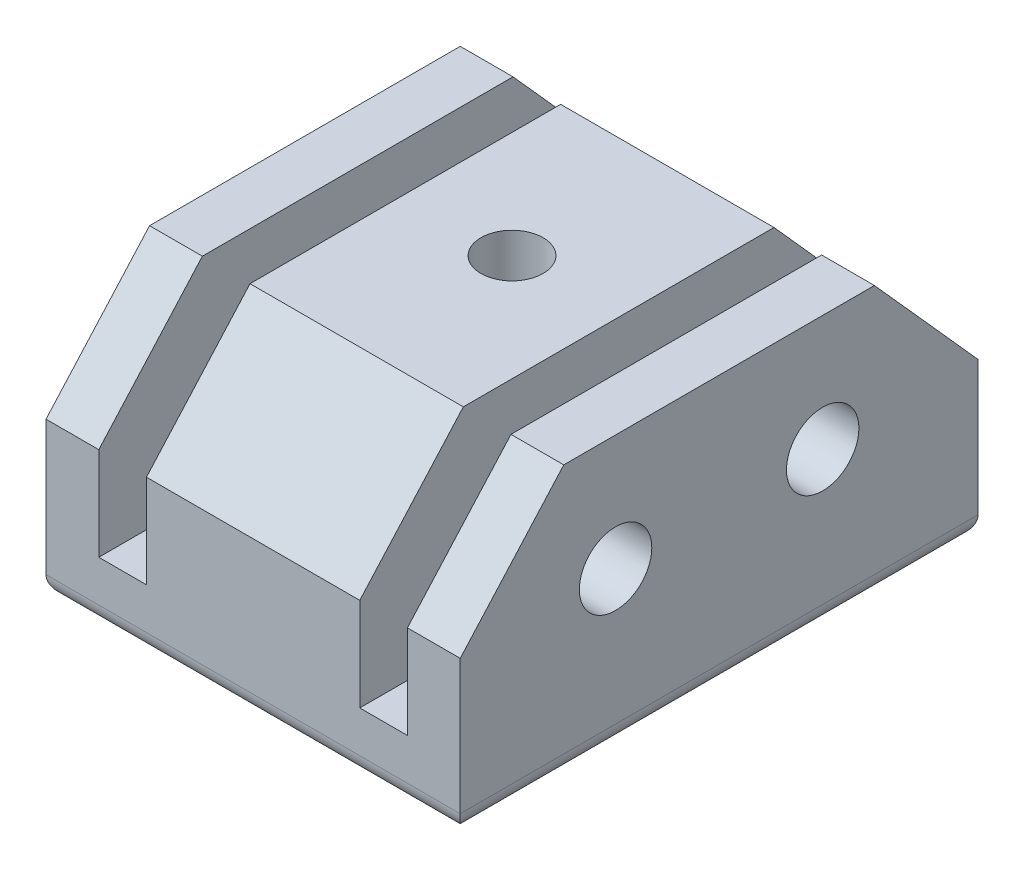
SolidWorks part; units mm, degrees
ref_plane "Front Plane" through (0, 0, 0) normal (0, 0, 1) x (1, 0, 0)
ref_plane "Top Plane" through (0, 0, 0) normal (0, 1, 0) x (1, 0, 0)
ref_plane "Right Plane" through (0, 0, 0) normal (1, 0, 0) x (0, 0, -1)
ref_plane "Plane3" through (-25.4, 0, 0) normal (1, 0, 0) x (0, 0, -1)
sketch "Sketch1" plane through (0, 0, 0) normal (1, 0, 0) x (0, 0, -1)
  line L1 (0, 0) -> (63.5, 0)
  line L2 (0, 0) -> (0, 6.35)
  line L3 (0, 6.35) -> (63.5, 6.35)
  line L4 (63.5, 0) -> (63.5, 6.35)
  dimension "D1" = 6.35
  dimension "D2" = 63.5
extrude "Boss-Extrude1" add sketch "Sketch1" against normal blind 50.8
sketch "Sketch2" plane through (0, 0, 0) normal (1, 0, 0) x (0, 0, -1)
  line L0 (0, 6.35) -> (0, 19.05)
  line L1 (0, 19.05) -> (12.7, 33.249)
  line L2 (12.7, 33.249) -> (50.8, 33.249)
  line L3 (50.8, 33.249) -> (63.5, 19.05)
  line L4 (63.5, 19.05) -> (63.5, 6.35)
  line L5 (63.5, 6.35) -> (0, 6.35)
  point P7 (31.75, 33.249)
  point P10 (31.75, 6.35)
  dimension "D1" = 38.1
  dimension "D2" = 12.7
  dimension "D3" = 12.7
  dimension "D4" = 19.05
  dimension "D5" = 19.05
extrude "Boss-Extrude2" add sketch "Sketch2" against normal blind 50.8
sketch "Sketch10" plane through (0, 0, -63.5) normal (0, 0, -1) x (-1, 0, 0)
  line L0 (25.4, 0) -> (25.4, 33.249) construction
  line L1 (50.8, 33.249) -> (0, 33.249) construction
  line L8 (50.8, 0) -> (0, 0) construction
  line L9 (12.319, 7.62) -> (38.481, 7.62) construction
  line L11 (12.319, 7.62) -> (6.477, 7.62)
  line L12 (12.319, 7.62) -> (12.319, 33.249)
  line L13 (12.319, 33.249) -> (6.477, 33.249)
  line L14 (6.477, 7.62) -> (6.477, 33.249)
  line L15 (38.481, 7.62) -> (44.323, 7.62)
  line L16 (38.481, 7.62) -> (38.481, 33.249)
  line L17 (38.481, 33.249) -> (44.323, 33.249)
  line L18 (44.323, 7.62) -> (44.323, 33.249)
  point P15 (25.4, 7.62)
  dimension "D1" = 7.62
  dimension "D2" = 5.842
  dimension "D3" = 5.842
  dimension "D4" = 26.162
extrude "Cut-Extrude1" cut sketch "Sketch10" against normal through all
sketch "Sketch11" plane through (0, 0, 0) normal (1, 0, 0) x (0, 0, -1)
  circle A0 centre (19.05, 19.05) radius 4.445
  circle A2 centre (44.45, 19.05) radius 4.445
  dimension "D1" = 8.89
  dimension "D2" = 6.35
  dimension "D5" = 6.35
extrude "Cut-Extrude2" cut sketch "Sketch11" against normal through all
ref_plane "Plane2" through (0, 33.02, 0) normal (0, -1, 0) x (-1, 0, 0)
fillet "Fillet1" radius 2.54 4 edges at (0, 0, -31.75) (-50.8, 0, -31.75) (-25.4, 0, 0) (-25.4, 0, -63.5)
sketch "Sketch24" plane through (0, 0, 0) normal (0, -1, 0) x (1, 0, 0)
  line L0 (-25.4, -63.5) -> (-25.4, 0) construction
  line L1 (-50.8, -63.5) -> (0, -63.5) construction
  line L2 (-50.8, 0) -> (0, 0) construction
  line L3 (0, -31.75) -> (-50.8, -31.75) construction
  line L4 (0, 0) -> (0, -63.5) construction
  line L5 (-50.8, 0) -> (-50.8, -63.5) construction
  circle A0 centre (-25.4, -31.75) radius 3.81
  dimension "D1" = 7.62
extrude "Cut-Extrude10" cut sketch "Sketch24" against normal through all
sketch "Sketch25" plane through (0, 0, 0) normal (0, -1, 0) x (1, 0, 0)
  line L1 (-29.3595, -24.892) -> (-33.3189, -31.75)
  line L2 (-33.3189, -31.75) -> (-29.3595, -38.608)
  line L3 (-29.3595, -38.608) -> (-21.4405, -38.608)
  line L4 (-21.4405, -38.608) -> (-17.4811, -31.75)
  line L5 (-17.4811, -31.75) -> (-21.4405, -24.892)
  line L6 (-21.4405, -24.892) -> (-29.3595, -24.892)
  circle A1 centre (-25.4, -31.75) radius 6.858 construction
extrude "Cut-Extrude11" cut sketch "Sketch25" against normal blind 6.35
